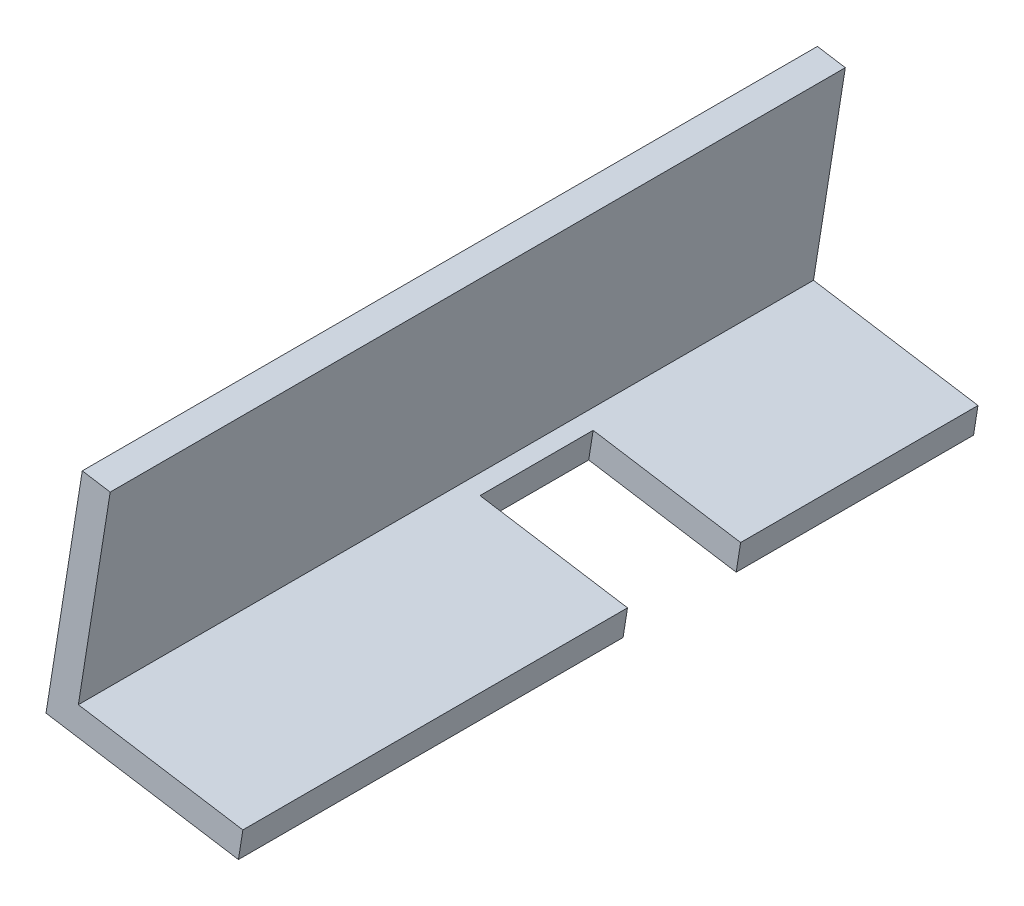
SolidWorks part; units mm, degrees
ref_plane "Front Plane" through (0, 0, 0) normal (0, 0, 1) x (1, 0, 0)
ref_plane "Top Plane" through (0, 0, 0) normal (0, 1, 0) x (1, 0, 0)
ref_plane "Right Plane" through (0, 0, 0) normal (1, 0, 0) x (0, 0, -1)
sketch "Sketch1" plane through (0, 0, 0) normal (0, 0, 1) x (1, 0, 0)
  line L7 (160.5406, 279.0398) -> (161.5382, 285.3109)
  line L8 (161.5382, 285.3109) -> (124.5929, 291.1886)
  line L9 (124.5929, 291.1886) -> (131.7406, 336.117)
  line L10 (131.7406, 336.117) -> (125.4695, 337.1146)
  line L11 (125.4695, 337.1146) -> (118.3216, 292.1863)
  line L12 (118.3216, 292.1863) -> (117.3237, 285.9152)
  line L13 (117.3237, 285.9152) -> (160.5406, 279.0398)
  line L14 (160.5406, 279.0398) -> (161.5382, 285.3109)
  line L15 (161.5382, 285.3109) -> (124.5929, 291.1886)
  line L16 (124.5929, 291.1886) -> (131.7406, 336.117)
  line L17 (131.7406, 336.117) -> (125.4695, 337.1146)
  line L18 (125.4695, 337.1146) -> (118.3216, 292.1863)
  line L19 (118.3216, 292.1863) -> (117.3237, 285.9152)
  line L20 (117.3237, 285.9152) -> (160.5406, 279.0398)
  dimension "D1" = 0
extrude "Boss-Extrude1" add sketch "Sketch1" against normal blind 165.1
sketch "Sketch2" plane through (48.2576, 303.3329, 0) normal (0.1571, 0.9876, 0) x (0.9876, -0.1571, 0)
  line L1 (81.1683, 111.7883) -> (115.2835, 111.7883)
  line L2 (81.1683, 111.7883) -> (81.1683, 86.3883)
  line L3 (81.1683, 86.3883) -> (115.2835, 86.3883)
  line L12 (115.2835, 111.7883) -> (115.2835, 86.3883)
extrude "Cut-Extrude1" cut sketch "Sketch2" against normal through all
